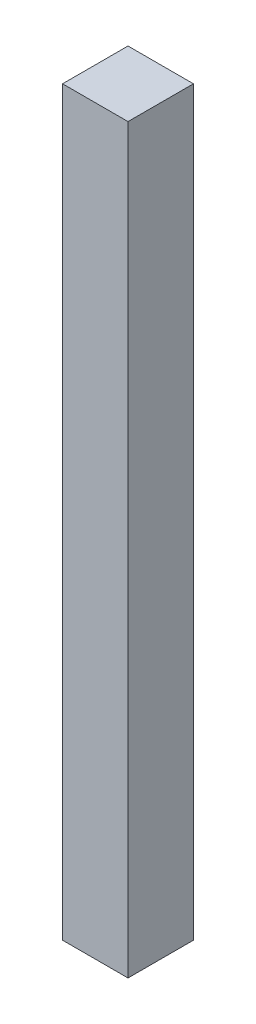
SolidWorks part; units mm, degrees
material "Hexcel AS4C (3000 Filaments)"
ref_plane "Front Plane" through (0, 0, 0) normal (0, 0, 1) x (1, 0, 0)
ref_plane "Top Plane" through (0, 0, 0) normal (0, 1, 0) x (1, 0, 0)
ref_plane "Right Plane" through (0, 0, 0) normal (1, 0, 0) x (0, 0, -1)
sketch "Sketch1" plane through (0, 0, 0) normal (0, 1, 0) x (1, 0, 0)
  line L1 (3, 3) -> (-3, 3)
  line L2 (3, 3) -> (3, -3)
  line L3 (3, -3) -> (-3, -3)
  line L4 (-3, 3) -> (-3, -3)
  line L5 (3, 3) -> (-3, -3) construction
  line L6 (3, -3) -> (-3, 3) construction
  point P0 (0, 0)
  dimension "D1" = 6
  dimension "D2" = 6
extrude "Boss-Extrude1" add sketch "Sketch1" along normal blind 68
